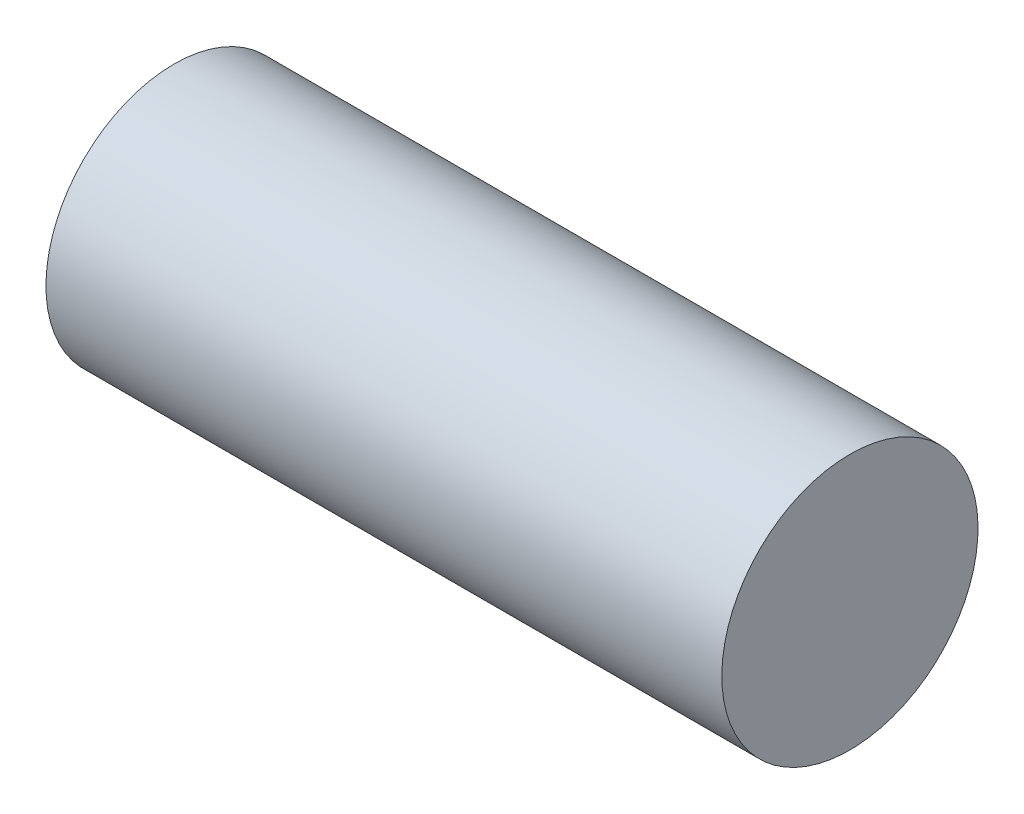
SolidWorks part; units mm, degrees
ref_plane "Ön Düzlem" through (0, 0, 0) normal (0, 0, 1) x (1, 0, 0)
ref_plane "Üst Düzlem" through (0, 0, 0) normal (0, 1, 0) x (1, 0, 0)
ref_plane "Sağ Düzlem" through (0, 0, 0) normal (1, 0, 0) x (0, 0, -1)
sketch "Sketch1" plane through (0, 0, 0) normal (0, 0, 1) x (1, 0, 0)
  line L0 (0, 0) -> (0, 1)
  line L1 (0, 1) -> (-1, 2)
  line L2 (-1, 2) -> (-7, 2)
  line L3 (-7, 2) -> (-7, 4)
  line L4 (-7, 4) -> (-10, 4)
  line L5 (-10, 4) -> (-10, 3)
  line L10 (-24.88, 5) -> (1.5, 5)
  line L11 (1.5, 5) -> (1.5, 0)
  line L12 (1.5, 0) -> (0, 0)
  line L13 (-24.88, 5) -> (-24.88, 4.5)
  line L14 (-24.88, 4.5) -> (-14.5, 4.5)
  line L15 (-14.5, 4.5) -> (-13, 3)
  line L16 (-13, 3) -> (-10, 3)
  dimension "D1" = 1
  dimension "D2" = 135
  dimension "D3" = 1
  dimension "D4" = 2
  dimension "D5" = 3
  dimension "D6" = 6
  dimension "D7" = 3
  dimension "D10" = 1.5
  dimension "D12" = 0.5
  dimension "D14" = 1.5
  dimension "D15" = 135
revolve "Revolve1" add sketch "Sketch1" angle 360 about L12
sketch "Sketch2" plane through (-7, 0, 0) normal (-1, 0, 0) x (0, 0, 1)
  line L0 (-2, 0) -> (-3.9, 0) construction
  line L1 (-2, -0.1) -> (-3.9, -0.1)
  line L2 (-2, 0.1) -> (-3.9, 0.1)
  circle A1 centre (0, 0) radius 2 construction
  arc A2 (-2, -0.1) -> (-2, 0.1) centre (-2, 0) ccw
  arc A3 (-3.9, 0.1) -> (-3.9, -0.1) centre (-3.9, 0) ccw
  point P8 (-2.95, 0)
  dimension "D1" = 0.1
  dimension "D2" = 1.9
extrude "Cut-Extrude1" cut sketch "Sketch2" against normal blind 0.5 and the other way blind 1.5
pattern_circular "CirPattern1" count 8 over 360 about axis through (0, 0, 0) along (1, 0, 0) of "Cut-Extrude1"
sketch "Sketch3" plane through (0, 0, 0) normal (-1, 0, 0) x (0, 0, 1)
  circle A0 centre (0, 0) radius 0.75
  circle A1 centre (0, 0) radius 0.625
  dimension "D1" = 1.5
  dimension "D2" = 1.25
extrude "Boss-Extrude1" add sketch "Sketch3" along normal blind 2.5
sketch "Sketch4" plane through (0, 0, 0) normal (-1, 0, 0) x (0, 0, 1)
  circle A0 centre (0, 0) radius 0.625
  dimension "D1" = 1.25
